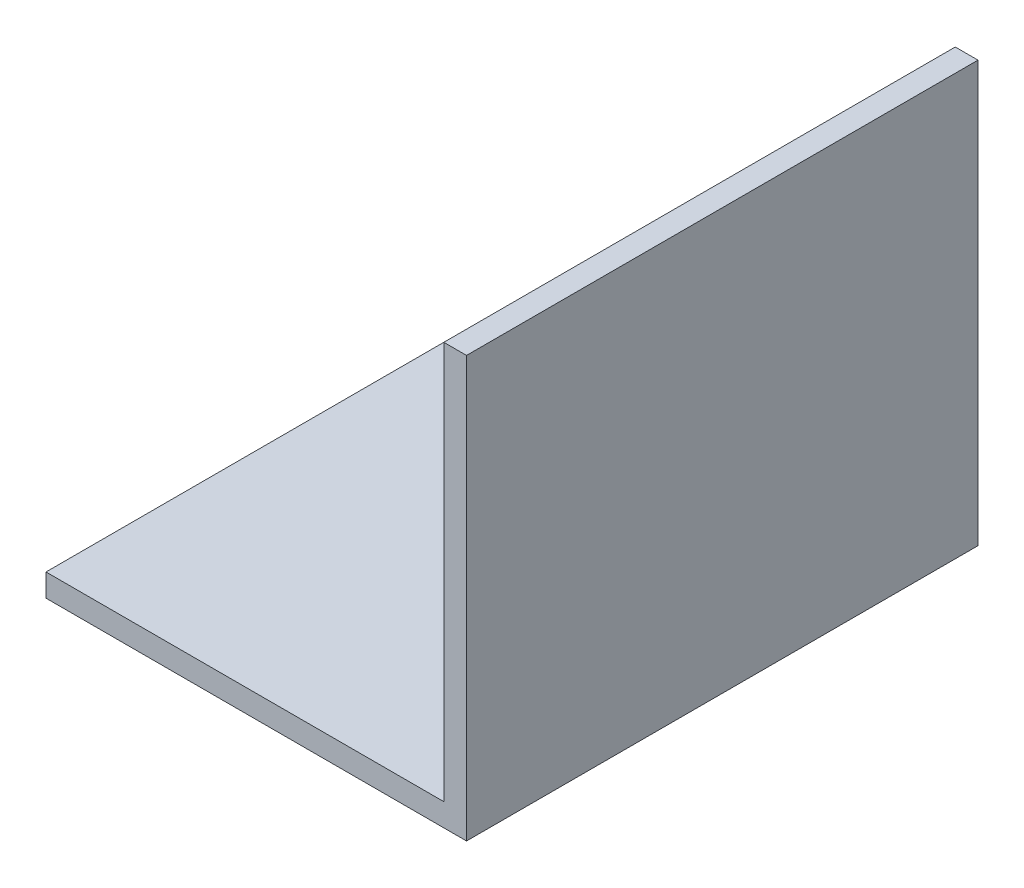
SolidWorks part; units mm, degrees
ref_plane "Front Plane" through (0, 0, 0) normal (0, 0, 1) x (1, 0, 0)
ref_plane "Top Plane" through (0, 0, 0) normal (0, 1, 0) x (1, 0, 0)
ref_plane "Right Plane" through (0, 0, 0) normal (1, 0, 0) x (0, 0, -1)
sketch "Sketch1" plane through (0, 0, 0) normal (0, 0, 1) x (1, 0, 0)
  line L0 (0, 37) -> (0, 0)
  line L1 (0, 0) -> (-37, 0)
  line L2 (-37, 0) -> (-37, 2)
  line L3 (-37, 2) -> (-2, 2)
  line L4 (-2, 2) -> (-2, 37)
  line L5 (-2, 37) -> (0, 37)
  dimension "D1" = 35
  dimension "D2" = 2
  dimension "D3" = 35
  dimension "D4" = 2
extrude "Boss-Extrude1" add sketch "Sketch1" along normal blind 45
